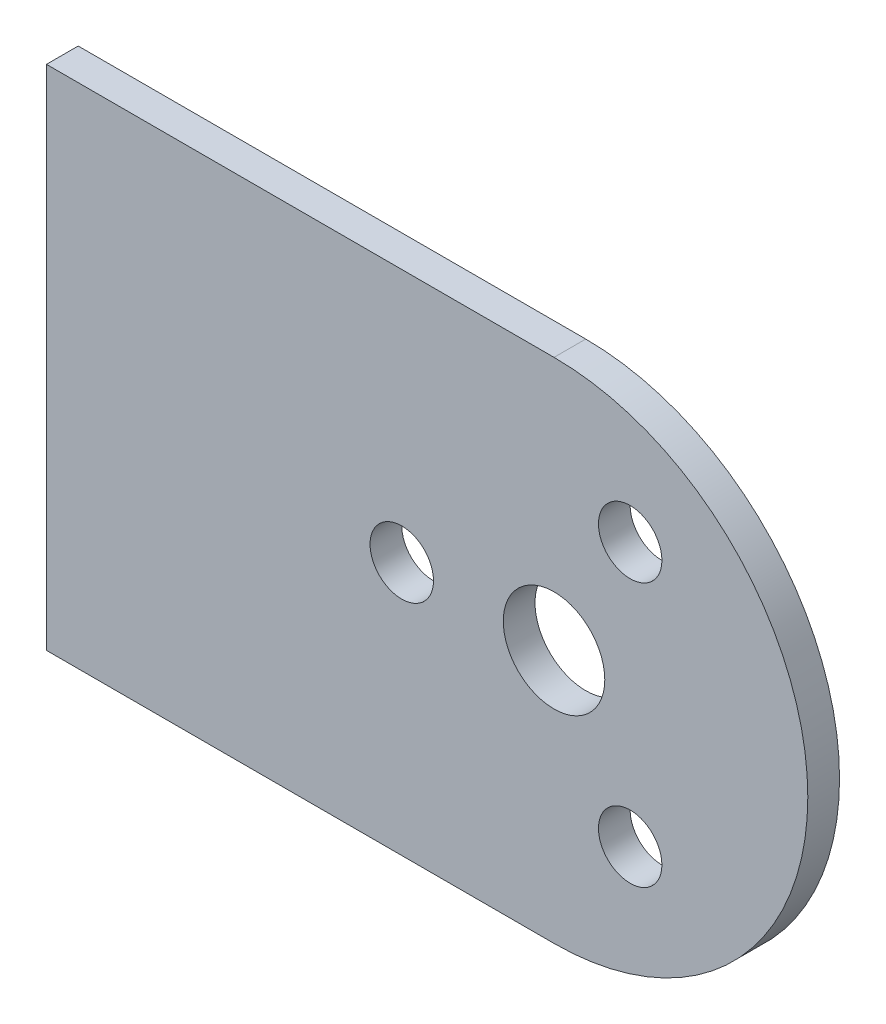
SolidWorks part; units mm, degrees
ref_plane "Front Plane" through (0, 0, 0) normal (0, 0, 1) x (1, 0, 0)
ref_plane "Top Plane" through (0, 0, 0) normal (0, 1, 0) x (1, 0, 0)
ref_plane "Right Plane" through (0, 0, 0) normal (1, 0, 0) x (0, 0, -1)
sketch "Sketch1" plane through (0, 0, 0) normal (0, 0, 1) x (1, 0, 0)
  line L0 (22.225, 50.6132) -> (-28.575, 50.6132)
  line L1 (-28.575, 50.6132) -> (-28.575, 101.4132)
  line L2 (-28.575, 101.4132) -> (22.225, 101.4132)
  circle A0 centre (22.225, 76.0132) radius 5.08
  circle A1 centre (6.985, 76.0132) radius 3.175
  circle A2 centre (29.845, 89.2115) radius 3.175
  circle A3 centre (29.845, 62.815) radius 3.175
  circle A4 centre (6.985, 76.0132) radius 3.175
  arc A5 (22.225, 50.6132) -> (22.225, 101.4132) centre (22.225, 76.0132) ccw
  point P3 (-28.575, 76.0132)
  point P11 (22.225, 76.0132)
  point P15 (0, 0)
  point P16 (0, 0)
  point P17 (0, 0)
  point P18 (0, 0)
  point P20 (0, 0)
  point P23 (5.3729, 73.1873)
  dimension "D4" = 10.16
  dimension "D5" = 6.35
  dimension "D6" = 25.4
  dimension "D2" = 50.8
  dimension "D3" = 15.24
  dimension "D7" = 50.6132
  dimension "D8" = 28.575
  dimension "D9" = 13.1982
  dimension "D1" = 3
extrude "Boss-Extrude1" add sketch "Sketch1" along normal blind 3.175 contours L0 A5 L2 L1 A0 A1 A2 A3
